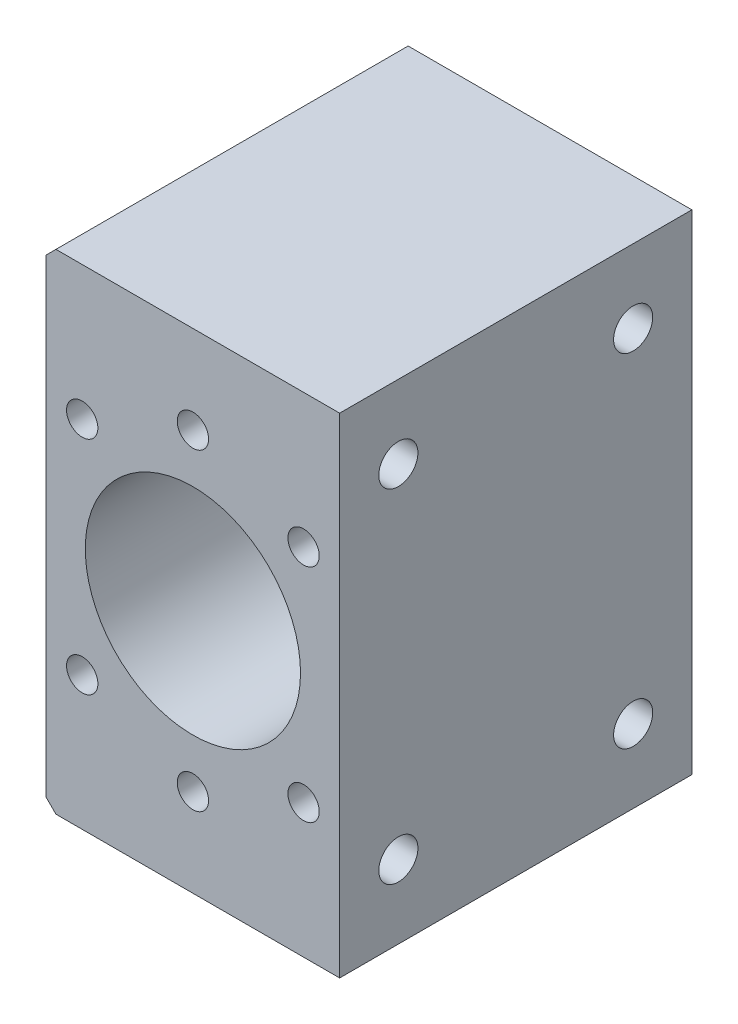
SolidWorks part; units mm, degrees
material "6061 合金"
ref_plane "前视基准面" through (0, 0, 0) normal (0, 0, 1) x (1, 0, 0)
ref_plane "上视基准面" through (0, 0, 0) normal (0, 1, 0) x (1, 0, 0)
ref_plane "右视基准面" through (0, 0, 0) normal (1, 0, 0) x (0, 0, -1)
sketch "草图4" plane through (0, 0, 0) normal (0, 0, 1) x (1, 0, 0)
  line L0 (-14, 25) -> (-15, 24)
  line L1 (-15, 25) -> (15, 25)
  line L2 (-15, 25) -> (-15, -25)
  line L3 (-15, -25) -> (15, -25)
  line L4 (15, 25) -> (15, -25)
  line L5 (0, -25) -> (0, 25) construction
  line L6 (-15, 0) -> (15, 0) construction
  line L7 (-14, -25) -> (-15, -24)
  circle A0 centre (0, 0) radius 11
  point P135 (0, 0)
  dimension "D1" = 50
  dimension "D2" = 22
  dimension "D3" = 1
  dimension "D4" = 1
  dimension "D5" = 30
extrude "凸台-拉伸2" add sketch "草图4" along normal blind 36 contours L7 L3 L4 L1 L0 L2 A0
sketch "草图5" plane through (0, 0, 36) normal (0, 0, 1) x (1, 0, 0)
  circle A0 centre (0, 0) radius 16 construction
  circle A1 centre (0, 16) radius 1.6
  circle A2 centre (11.3137, 11.3137) radius 1.6
  circle A3 centre (16, 0) radius 1.6 construction
  circle A4 centre (11.3137, -11.3137) radius 1.6
  circle A5 centre (0, -16) radius 1.6
  circle A6 centre (-11.3137, -11.3137) radius 1.6
  circle A7 centre (-16, 0) radius 1.6 construction
  circle A8 centre (-11.3137, 11.3137) radius 1.6
  point P22 (0, 0)
  dimension "D1" = 32
  dimension "D2" = 3.2
  dimension "D3" = 8
extrude "切除-拉伸2" cut sketch "草图5" against normal blind 10
cosmetic thread "装饰螺纹线1" parameters "D2"=4
cosmetic thread "装饰螺纹线2" parameters "D2"=4
cosmetic thread "装饰螺纹线3" parameters "D2"=4
cosmetic thread "装饰螺纹线4" parameters "D2"=4
cosmetic thread "装饰螺纹线5" parameters "D2"=4
cosmetic thread "装饰螺纹线6" parameters "D2"=4
sketch "草图6" plane through (15, 0, 0) normal (1, 0, 0) x (0, 0, -1)
  line L0 (-36, 25) -> (-36, -25) construction
  line L5 (-30, 17.5) -> (-6, 17.5) construction
  line L6 (-30, 17.5) -> (-30, -17.5) construction
  line L7 (-30, -17.5) -> (-6, -17.5) construction
  line L8 (-6, 17.5) -> (-6, -17.5) construction
  line L9 (-18, -17.5) -> (-18, 17.5) construction
  line L10 (-30, 0) -> (-6, 0) construction
  circle A0 centre (-6, 17.5) radius 2
  circle A1 centre (-30, 17.5) radius 2
  circle A2 centre (-30, -17.5) radius 2
  circle A3 centre (-6, -17.5) radius 2
  point P92 (-18, 0)
  dimension "D4" = 4
  dimension "D1" = 6
  dimension "D2" = 24
  dimension "D3" = 35
extrude "切除-拉伸3" cut sketch "草图6" against normal blind 10
cosmetic thread "装饰螺纹线7" parameters "D2"=5
cosmetic thread "装饰螺纹线8" parameters "D2"=5
cosmetic thread "装饰螺纹线9" parameters "D2"=5
cosmetic thread "装饰螺纹线10" parameters "D2"=5
sketch "草图9" plane through (-15, 0, 0) normal (-1, 0, 0) x (0, 0, 1)
  circle A13 centre (6, 17.5) radius 1.2
  circle A14 centre (6, -17.5) radius 2
  circle A15 centre (6, -17.5) radius 2 construction
  circle A16 centre (30, -17.5) radius 2
  circle A17 centre (30, -17.5) radius 2 construction
  circle A18 centre (30, 17.5) radius 2
  circle A19 centre (30, 17.5) radius 2 construction
  circle A20 centre (6, 17.5) radius 2
  circle A21 centre (6, 17.5) radius 2 construction
  circle A22 centre (30, 17.5) radius 1.2
  circle A23 centre (6, -17.5) radius 1.2
  circle A24 centre (30, -17.5) radius 1.2
  dimension "D5" = 2.4
  dimension "D1" = 0
  dimension "D2" = 0
  dimension "D3" = 0
  dimension "D4" = 0
extrude "切除-拉伸5" cut sketch "草图9" against normal blind 5
cosmetic thread "装饰螺纹线19" parameters "D2"=3
cosmetic thread "装饰螺纹线20" parameters "D2"=3
cosmetic thread "装饰螺纹线21" parameters "D2"=3
cosmetic thread "装饰螺纹线22" parameters "D2"=3
